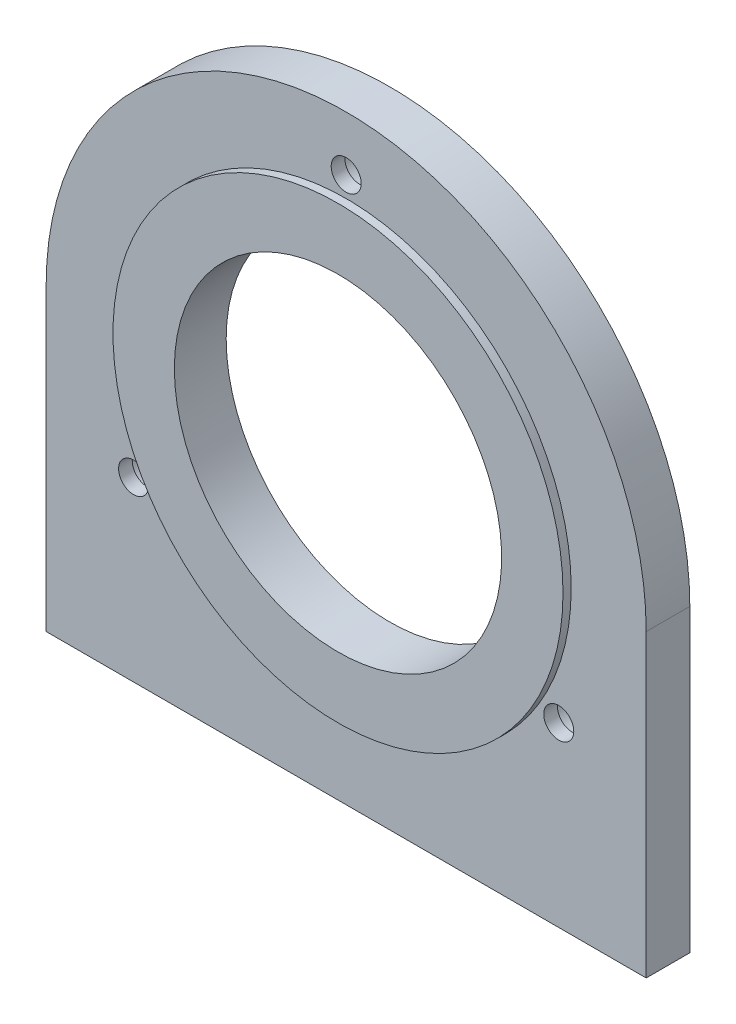
SolidWorks part; units mm, degrees
material "Q235A"
ref_plane "前视" through (0, 0, 0) normal (0, 0, 1) x (1, 0, 0)
ref_plane "上视" through (0, 0, 0) normal (0, 1, 0) x (1, 0, 0)
ref_plane "右视" through (0, 0, 0) normal (1, 0, 0) x (0, 0, -1)
sketch "草图1" plane through (0, 0, 0) normal (0, 0, 1) x (1, 0, 0)
  circle A0 centre (0, 0) radius 110
  dimension "D1" = 220
extrude "凸台-拉伸1" add sketch "草图1" along normal blind 16
sketch "草图2" plane through (0, 0, 16) normal (0, 0, 1) x (1, 0, 0)
  line L0 (50, 0) -> (-50, 0) construction
  line L1 (-110, 0) -> (110, 0)
  line L2 (-110, 0) -> (-110, -110)
  line L3 (-110, -110) -> (110, -110)
  line L4 (110, 0) -> (110, -110)
  circle A0 centre (0, 0) radius 110 construction
  dimension "D1" = 110
extrude "凸台-拉伸2" add sketch "草图2" against normal up to surface (16 mm away) up to face at (110, 0, 0)
sketch "草图3" plane through (0, 0, 16) normal (0, 0, 1) x (1, 0, 0)
  circle A0 centre (0, 0) radius 82.5
  dimension "D1" = 165
extrude "凸台-拉伸3" add sketch "草图3" along normal blind 3
hole_wizard "打孔尺寸(%根据)内六角圆柱头螺钉的类型1" positions "草图5" profile "草图4" counterbore size "M10" standard "GB" end condition through all
sketch "草图5" plane through (0, 0, 0) normal (0, 0, -1) x (-1, 0, 0)
  line L0 (50, 0) -> (-50, 0) construction
  point P0 (0, 90)
  dimension "D1" = 90
sketch "草图4" plane through (0, 90, 0) normal (1, 0, 0) x (0, 1, 0)
  line L0 (0, 0) -> (0, 19)
  line L1 (0, 19) -> (5.5, 19)
  line L3 (5.5, 19) -> (5.5, 11)
  line L4 (5.5, 11) -> (9, 11)
  line L5 (9, 11) -> (9, 0)
  line L7 (9, 0) -> (0, 0)
  line L11 (0, -6.35) -> (0, 107.95) construction
  dimension "通孔孔直径" = 11
  dimension "通孔孔深度" = 19
  dimension "柱形沉头孔直径" = 18
  dimension "柱形沉头孔深度" = 11
pattern_circular "阵列(圆周)1" count 3 over 360 about axis through (0, 0, 0) along (0, 0, 1) of "打孔尺寸(%根据)内六角圆柱头螺钉的类型1"
sketch "草图6" plane through (0, 0, 0) normal (0, 0, -1) x (-1, 0, 0)
  circle A0 centre (0, 0) radius 60
  dimension "D1" = 120
extrude "切除-拉伸1" cut sketch "草图6" against normal through all
